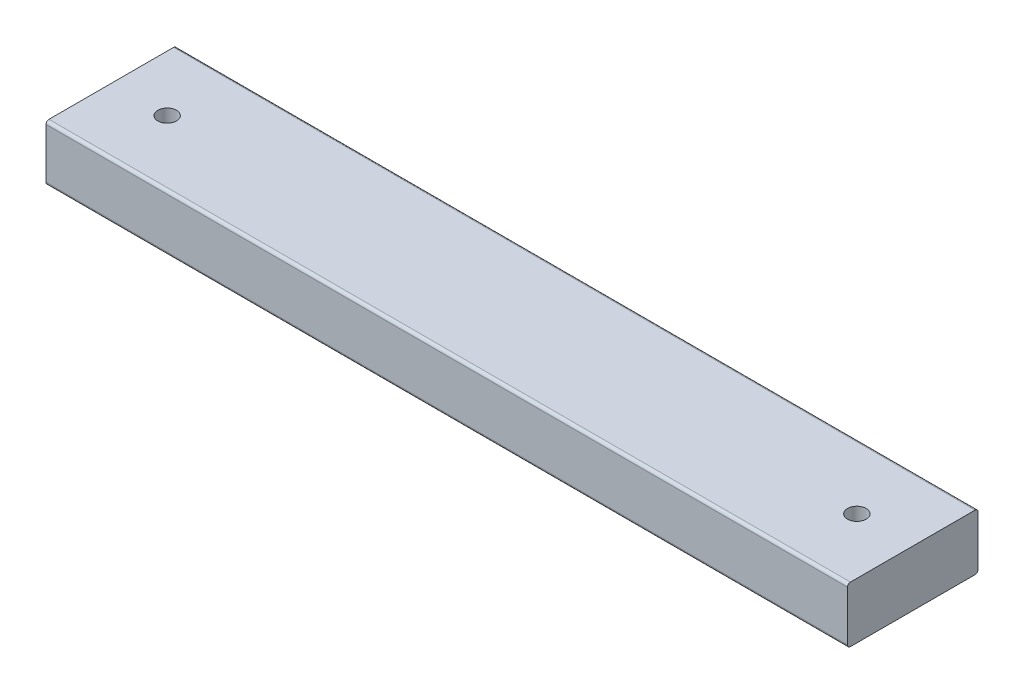
SolidWorks part; units mm, degrees
ref_plane "Front Plane" through (0, 0, 0) normal (0, 0, 1) x (1, 0, 0)
ref_plane "Top Plane" through (0, 0, 0) normal (0, 1, 0) x (1, 0, 0)
ref_plane "Right Plane" through (0, 0, 0) normal (1, 0, 0) x (0, 0, -1)
sketch "Sketch1" plane through (0, 0, 0) normal (1, 0, 0) x (0, 0, -1)
  line L1 (-44.45, -19.05) -> (44.45, -19.05)
  line L2 (-44.45, -19.05) -> (-44.45, 19.05)
  line L3 (-44.45, 19.05) -> (44.45, 19.05)
  line L4 (44.45, -19.05) -> (44.45, 19.05)
  line L5 (-44.45, -19.05) -> (44.45, 19.05) construction
  line L6 (-44.45, 19.05) -> (44.45, -19.05) construction
  point P0 (0, 0)
  dimension "D1" = 38.1
  dimension "D2" = 88.9
extrude "Boss-Extrude1" add sketch "Sketch1" along normal blind 546.1
fillet "Fillet1" radius 2 4 edges at (273.05, 19.05, 44.45) (273.05, 19.05, -44.45) (273.05, -19.05, -44.45) (273.05, -19.05, 44.45)
sketch "Sketch2" plane through (0, 19.05, 0) normal (0, 1, 0) x (1, 0, 0)
  line L0 (0, 0) -> (38.1, 0) construction
  line L1 (38.1, 0) -> (508, 0) construction
  line L2 (508, 0) -> (546.1, 0) construction
  line L4 (546.1, 42.45) -> (546.1, -42.45) construction
  circle A0 centre (38.1, 0) radius 6.35
  circle A1 centre (508, 0) radius 6.35
  dimension "D1" = 12.7
  dimension "D2" = 38.1
extrude "Cut-Extrude1" cut sketch "Sketch2" against normal through all
